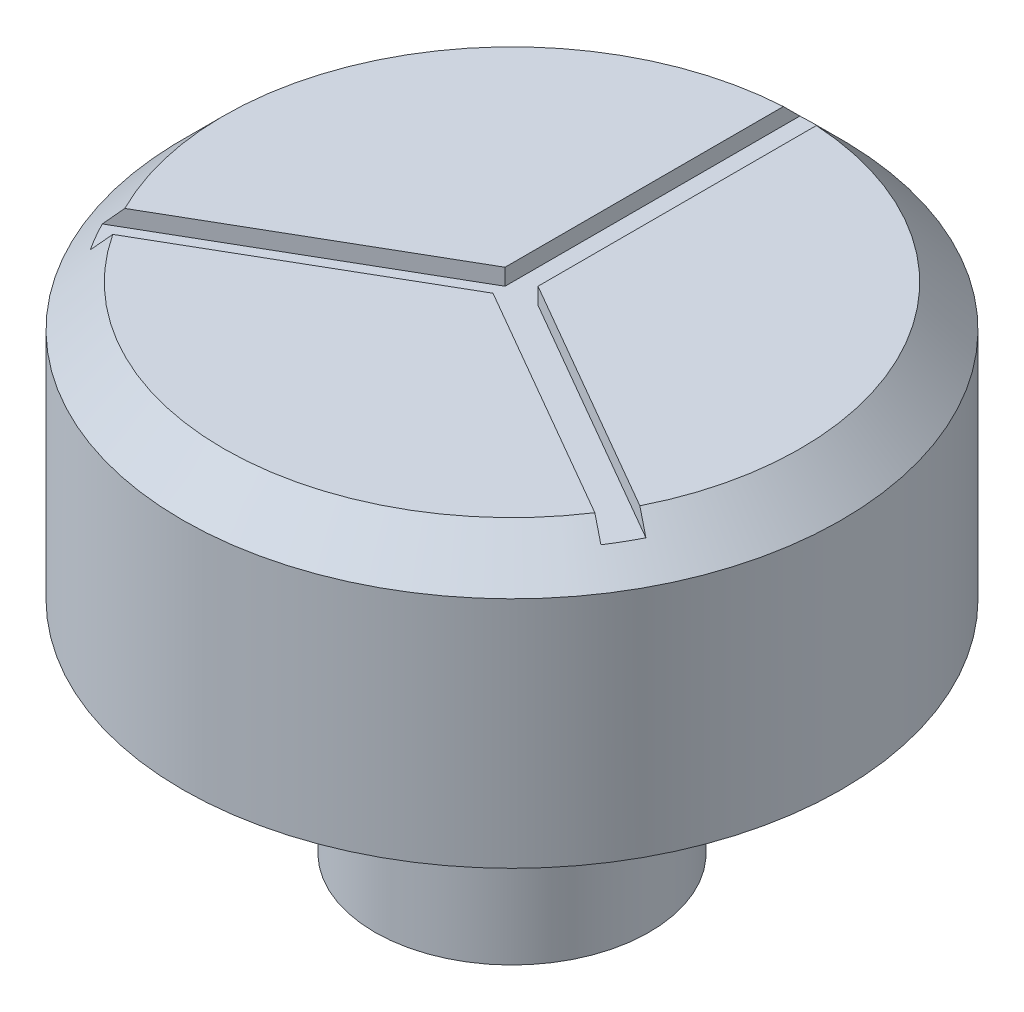
SolidWorks part; units mm, degrees
ref_plane "Front Plane" through (0, 0, 0) normal (0, 0, 1) x (1, 0, 0)
ref_plane "Top Plane" through (0, 0, 0) normal (0, 1, 0) x (1, 0, 0)
ref_plane "Right Plane" through (0, 0, 0) normal (1, 0, 0) x (0, 0, -1)
sketch "Sketch1" plane through (0, 0, 0) normal (0, 1, 0) x (1, 0, 0)
  circle A0 centre (0, 0) radius 25
  dimension "D1" = 50
extrude "Boss-Extrude1" add sketch "Sketch1" along normal blind 40
sketch "Sketch2" plane through (0, 40, 0) normal (0, 1, 0) x (1, 0, 0)
  circle A0 centre (0, 0) radius 60
  dimension "D1" = 120
extrude "Boss-Extrude2" add sketch "Sketch2" along normal blind 50
ref_point "Point1"
chamfer "Chamfer1" distance 7.5 angle 45 1 edges at (0, 90, 60)
sketch "Sketch3" plane through (0, 90, 0) normal (0, 1, 0) x (1, 0, 0)
  line L0 (0, 60) -> (0, 0) construction
  line L1 (0, 0) -> (-51.9615, -30) construction
  line L2 (0, 0) -> (51.9615, -30) construction
  line L3 (-51.9615, -30) -> (0, 60) construction
  line L4 (0, 60) -> (51.9615, -30) construction
  line L5 (51.9615, -30) -> (-51.9615, -30) construction
  line L6 (-3, 1.7321) -> (-53.4615, -27.4019)
  line L7 (-3, 60) -> (-3, 1.7321)
  line L8 (0, -3.4641) -> (50.4615, -32.5981)
  line L9 (0, -3.4641) -> (-50.4615, -32.5981)
  line L10 (3, 60) -> (3, 1.7321)
  line L11 (3, 1.7321) -> (53.4615, -27.4019)
  line L12 (-1.5, 2.5981) -> (-53.4615, -27.4019) construction
  line L13 (-3, 60) -> (-3, 0) construction
  line L14 (1.5, 2.5981) -> (53.4615, -27.4019) construction
  line L15 (3, 60) -> (3, 0) construction
  line L16 (1.5, -2.5981) -> (-50.4615, -32.5981) construction
  line L17 (-1.5, -2.5981) -> (50.4615, -32.5981) construction
  circle A0 centre (0, 0) radius 60 construction
  arc A2 (-53.4615, -27.4019) -> (-50.4615, -32.5981) centre (-51.9615, -30) ccw
  arc A3 (-3, 60) -> (3, 60) centre (0, 60) cw
  arc A6 (50.4615, -32.5981) -> (53.4615, -27.4019) centre (51.9615, -30) ccw
  dimension "D1" = 3
  dimension "D2" = 3
extrude "Cut-Extrude1" cut sketch "Sketch3" against normal blind 3
